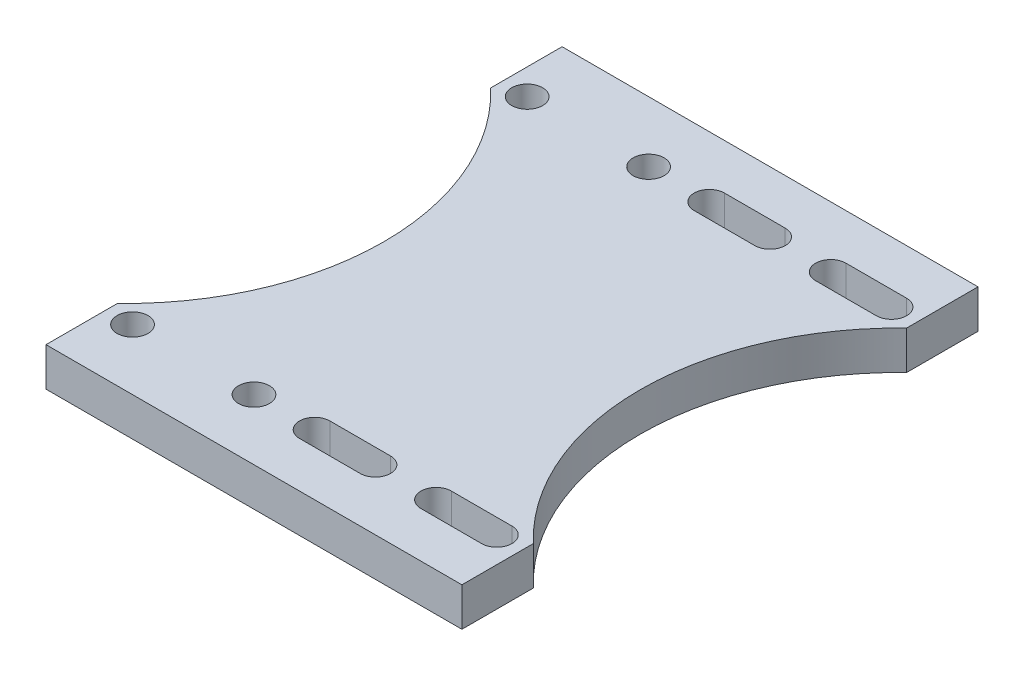
SolidWorks part; units mm, degrees
ref_plane "Front Plane" through (0, 0, 0) normal (0, 0, 1) x (1, 0, 0)
ref_plane "Top Plane" through (0, 0, 0) normal (0, 1, 0) x (1, 0, 0)
ref_plane "Right Plane" through (0, 0, 0) normal (1, 0, 0) x (0, 0, -1)
sketch "Sketch1" plane through (0, 0, 0) normal (0, 1, 0) x (1, 0, 0)
  line L16 (0, 32.5) -> (-30.75, 32.5) construction
  line L19 (-30.75, 32.5) -> (-30.75, -32.5) construction
  line L24 (-30.75, -32.5) -> (0, -32.5) construction
  line L27 (0, -42.5) -> (-35, -42.5)
  line L33 (-35, 42.5) -> (0, 42.5)
  line L34 (0, 42.5) -> (0, -42.5) construction
  line L35 (0, 0) -> (-64.3552, 0) construction
  line L37 (-35, 42.5) -> (-35, -42.5) construction
  line L38 (-35, 42.5) -> (-35, 30.733)
  line L40 (-35, -30.733) -> (-35, -42.5)
  line L41 (-10.75, 32.5) -> (-10.75, -32.5) construction
  line L43 (0, 42.5) -> (33.5, 42.5)
  line L44 (33.5, 42.5) -> (33.5, 32.5)
  line L45 (33.5, -42.5) -> (0, -42.5)
  line L47 (0, 32.5) -> (33.5, 32.5) construction
  line L48 (29.25, -32.5) -> (19.25, -32.5) construction
  line L49 (0, -32.5) -> (33.5, -32.5) construction
  line L50 (29.25, -35) -> (19.25, -35)
  line L51 (29.25, -30) -> (19.25, -30)
  line L52 (9.25, -32.5) -> (-0.75, -32.5) construction
  line L53 (9.25, -35) -> (-0.75, -35)
  line L54 (9.25, -30) -> (-0.75, -30)
  line L55 (29.25, 32.5) -> (19.25, 32.5) construction
  line L56 (29.25, 30) -> (19.25, 30)
  line L57 (29.25, 35) -> (19.25, 35)
  line L58 (9.25, 32.5) -> (-0.75, 32.5) construction
  line L59 (9.25, 30) -> (-0.75, 30)
  line L60 (9.25, 35) -> (-0.75, 35)
  line L61 (29.25, 32.5) -> (29.25, -32.5) construction
  line L62 (0, 0) -> (62.8552, 0) construction
  line L63 (9.25, 32.5) -> (9.25, -32.5) construction
  line L64 (33.5, -32.5) -> (33.5, -42.5)
  line L65 (33.5, 32.5) -> (33.5, -32.5) construction
  line L66 (33.5, 32.5) -> (33.5, 30.733)
  line L68 (33.5, -30.733) -> (33.5, -32.5)
  circle A60 centre (-30.75, -32.5) radius 2.55
  circle A61 centre (-30.75, -32.5) radius 4.25 construction
  circle A62 centre (-30.75, 32.5) radius 2.55
  circle A63 centre (-64.3552, 0) radius 42.5 construction
  arc A64 (-35, 30.733) -> (-35, -30.733) centre (-64.3552, 0) cw
  circle A65 centre (-10.75, 32.5) radius 2.55
  circle A66 centre (-10.75, -32.5) radius 2.55
  arc A67 (29.25, -35) -> (29.25, -30) centre (29.25, -32.5) ccw
  arc A68 (19.25, -30) -> (19.25, -35) centre (19.25, -32.5) ccw
  arc A69 (9.25, -35) -> (9.25, -30) centre (9.25, -32.5) ccw
  arc A70 (-0.75, -30) -> (-0.75, -35) centre (-0.75, -32.5) ccw
  arc A71 (29.25, 30) -> (29.25, 35) centre (29.25, 32.5) ccw
  arc A72 (19.25, 35) -> (19.25, 30) centre (19.25, 32.5) ccw
  arc A73 (9.25, 30) -> (9.25, 35) centre (9.25, 32.5) ccw
  arc A74 (-0.75, 35) -> (-0.75, 30) centre (-0.75, 32.5) ccw
  circle A76 centre (29.25, 32.5) radius 4.25 construction
  arc A77 (33.5, -30.733) -> (33.5, 30.733) centre (62.8552, 0) cw
  circle A78 centre (62.8552, 0) radius 42.5 construction
  point P26 (24.25, -32.5)
  point P31 (4.25, -32.5)
  point P38 (24.25, 32.5)
  point P45 (4.25, 32.5)
  dimension "D1" = 85
  dimension "D2" = 8.5
  dimension "D4" = 85
  dimension "D5" = 10
  dimension "D6" = 10
  dimension "D7" = 20
  dimension "D9" = 5
  dimension "D10" = 20
  dimension "D8" = 10
  dimension "D11" = 20
  dimension "D12" = 35
  dimension "D13" = 8.5
  dimension "D14" = 85
  dimension "D3" = 5.1
extrude "Boss-Extrude1" add sketch "Sketch1" against normal blind 6.35
